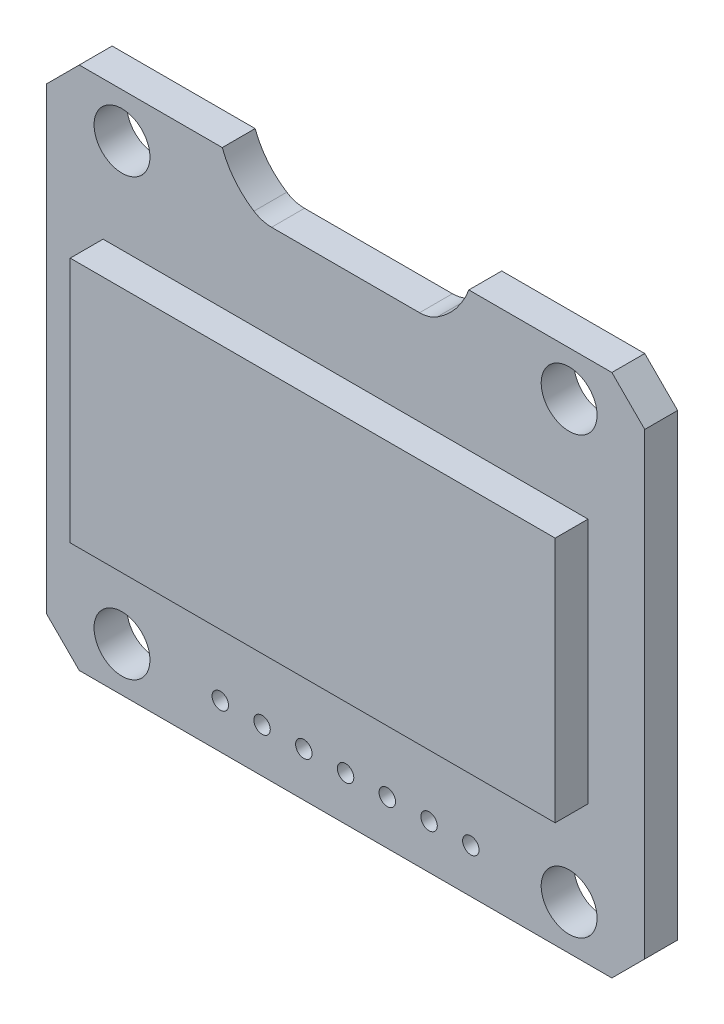
SolidWorks part; units mm, degrees
ref_plane "前视基准面" through (0, 0, 0) normal (0, 0, 1) x (1, 0, 0)
ref_plane "上视基准面" through (0, 0, 0) normal (0, 1, 0) x (1, 0, 0)
ref_plane "右视基准面" through (0, 0, 0) normal (1, 0, 0) x (0, 0, -1)
other "Configuration Table"
sketch "草图1" plane through (0, 0, 0) normal (0, 0, 1) x (1, 0, 0)
  line L1 (-18.2, -15.95) -> (18.2, -15.95)
  line L2 (-18.2, -15.95) -> (-18.2, 15.95)
  line L3 (-18.2, 15.95) -> (18.2, 15.95)
  line L4 (18.2, -15.95) -> (18.2, 15.95)
  line L5 (-18.2, -15.95) -> (18.2, 15.95) construction
  line L6 (-18.2, 15.95) -> (18.2, -15.95) construction
  point P0 (0, 0)
  dimension "D1" = 36.4
  dimension "D2" = 31.9
extrude "凸台-拉伸1" add sketch "草图1" along normal blind 2
sketch "草图2" plane through (0, 0, 2) normal (0, 0, 1) x (1, 0, 0)
  line L1 (-14.75, -7.5) -> (14.75, -7.5)
  line L2 (-14.75, -7.5) -> (-14.75, 7.5)
  line L3 (-14.75, 7.5) -> (14.75, 7.5)
  line L4 (14.75, -7.5) -> (14.75, 7.5)
  line L5 (-14.75, -7.5) -> (14.75, 7.5) construction
  line L6 (-14.75, 7.5) -> (14.75, -7.5) construction
  point P0 (0, 0)
  dimension "D1" = 29.5
  dimension "D2" = 15
extrude "凸台-拉伸2" add sketch "草图2" along normal blind 2
sketch "草图3" plane through (0, 0, 2) normal (0, 0, 1) x (1, 0, 0)
  line L0 (0, 15.95) -> (0, 0) construction
  line L1 (18.2, 15.95) -> (-18.2, 15.95) construction
  line L2 (0, 0) -> (18.2, 0) construction
  line L3 (18.2, -15.95) -> (18.2, 15.95) construction
  circle A0 centre (-13.6, 13.25) radius 1.7
  circle A1 centre (13.6, 13.25) radius 1.7
  circle A2 centre (13.6, -13.25) radius 1.7
  circle A3 centre (-13.6, -13.25) radius 1.7
  dimension "D1" = 3.4
  dimension "D2" = 26.5
  dimension "D3" = 27.2
extrude "切除-拉伸2" cut sketch "草图3" against normal blind 2
sketch "草图4" plane through (0, 0, 2) normal (0, 0, 1) x (1, 0, 0)
  line L0 (-16.2, 15.95) -> (-18.2, 13.95)
  line L1 (18.2, 15.95) -> (-18.2, 15.95) construction
  line L2 (-18.2, 15.95) -> (-18.2, -15.95) construction
  line L3 (0, 15.95) -> (0, 0) construction
  line L4 (0, 0) -> (18.2, 0) construction
  line L5 (18.2, -15.95) -> (18.2, 15.95) construction
  line L6 (-18.2, 15.95) -> (-16.2, 15.95)
  line L7 (-18.2, 13.95) -> (-18.2, 15.95)
  line L8 (18.2, 13.95) -> (18.2, 15.95)
  line L9 (18.2, 15.95) -> (16.2, 15.95)
  line L10 (16.2, 15.95) -> (18.2, 13.95)
  line L11 (16.2, -15.95) -> (18.2, -13.95)
  line L12 (18.2, -15.95) -> (16.2, -15.95)
  line L13 (18.2, -13.95) -> (18.2, -15.95)
  line L14 (-18.2, -13.95) -> (-18.2, -15.95)
  line L15 (-18.2, -15.95) -> (-16.2, -15.95)
  line L16 (-16.2, -15.95) -> (-18.2, -13.95)
  dimension "D1" = 2
  dimension "D2" = 45
extrude "切除-拉伸3" cut sketch "草图4" against normal blind 2
sketch "草图5" plane through (0, 0, 2) normal (0, 0, 1) x (1, 0, 0)
  line L0 (0, 0) -> (0, -13.25) construction
  line L1 (-13.6, -13.25) -> (-7.62, -13.25) construction
  circle A0 centre (-7.62, -13.25) radius 0.5
  circle A1 centre (-5.08, -13.25) radius 0.5
  circle A2 centre (-2.54, -13.25) radius 0.5
  circle A3 centre (0, -13.25) radius 0.5
  circle A4 centre (2.54, -13.25) radius 0.5
  circle A5 centre (5.08, -13.25) radius 0.5
  circle A6 centre (7.62, -13.25) radius 0.5
  dimension "D1" = 1
  dimension "D3" = 2.54
  dimension "D2" = 7
extrude "切除-拉伸4" cut sketch "草图5" against normal blind 30
sketch "草图6" plane through (0, 0, 2) normal (0, 0, 1) x (1, 0, 0)
  line L1 (16.2, 15.95) -> (-16.2, 15.95) construction
  line L2 (-5, 13.25) -> (5, 13.25)
  line L3 (0, 13.25) -> (0, 15.95) construction
  line L4 (-7.5, 15.95) -> (7.5, 15.95)
  line L5 (-5, 13.25) -> (-13.6, 13.25) construction
  arc A0 (-7.5, 15.95) -> (-5, 13.25) centre (-3, 17.6093) ccw
  arc A1 (7.5, 15.95) -> (5, 13.25) centre (3, 17.6093) cw
  dimension "D1" = 15
  dimension "D2" = 10
  dimension "D3" = 6
extrude "切除-拉伸5" cut sketch "草图6" against normal blind 10
fillet "圆角1" radius 2 2 edges at (-5, 13.25, 1) (5, 13.25, 1)
